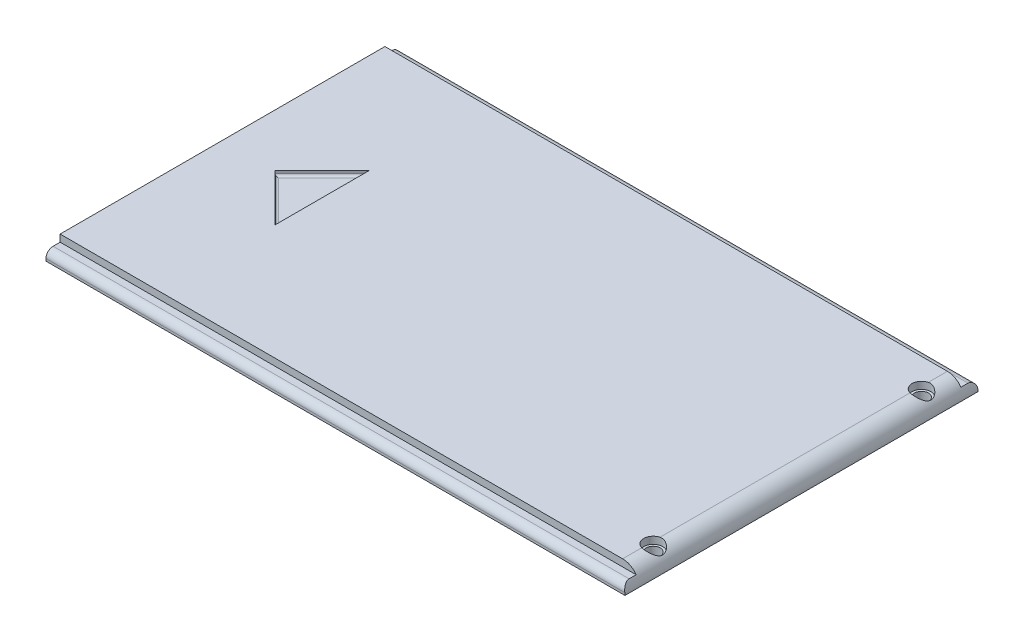
SolidWorks part; units mm, degrees
ref_plane "Front" through (0, 0, 0) normal (0, 0, 1) x (1, 0, 0)
ref_plane "Top" through (0, 0, 0) normal (0, 1, 0) x (1, 0, 0)
ref_plane "Right" through (0, 0, 0) normal (1, 0, 0) x (0, 0, -1)
sketch "Sketch1" plane through (0, 0, 0) normal (0, 1, 0) x (1, 0, 0)
  line L1 (-55, 37.5) -> (68, 37.5)
  line L2 (-55, 37.5) -> (-55, -37.5)
  line L3 (-55, -37.5) -> (68, -37.5)
  line L4 (68, 37.5) -> (68, -37.5)
  dimension "D1" = 37.5
  dimension "D2" = 75
  dimension "D3" = 123
  dimension "D4" = 55
extrude "Boss-Extrude1" add sketch "Sketch1" against normal blind 3.5
sketch "Sketch2" plane through (0, 0, 0) normal (0, 1, 0) x (1, 0, 0)
  line L0 (68, -37.5) -> (68, 37.5) construction
  line L1 (-55, 37.5) -> (68, 37.5)
  line L2 (-55, 37.5) -> (-55, 34.5)
  line L3 (-55, 34.5) -> (68, 34.5)
  line L4 (68, 37.5) -> (68, 34.5)
  line L6 (-55, -37.5) -> (68, -37.5)
  line L7 (-55, -37.5) -> (-55, -34.5)
  line L8 (-55, -34.5) -> (68, -34.5)
  line L9 (68, -37.5) -> (68, -34.5)
  dimension "D1" = 3
  dimension "D2" = 3
extrude "Cut-Extrude2" cut sketch "Sketch2" against normal blind 1.5
fillet "Fillet1" radius 1.5 1 edges at (6.5, -1.5, 37.5)
fillet "Fillet2" radius 1.5 1 edges at (6.5, -1.5, -37.5)
fillet "Fillet3" radius 3.5 9 edges at (68, 0, 0) (68, -1.5, -35.25) (68, -0.75, -34.5) (68, -0.75, 34.5) (68, -1.5, 35.25) (68, -1.9393, 37.0607) (68, -1.9393, -37.0607) (68, -3.25, -37.5) (68, -3.25, 37.5)
sketch "Sketch3" plane through (0, 0, 0) normal (0, 1, 0) x (1, 0, 0)
  line L0 (-43.8527, 0) -> (-33.8527, -10)
  line L1 (-33.8527, -10) -> (-33.8527, 10)
  line L2 (-33.8527, 10) -> (-43.8527, 0)
  point P2 (-33.8527, 0)
  dimension "D1" = 20
  dimension "D2" = 0
extrude "Cut-Extrude3" cut sketch "Sketch3" against normal blind 1
fillet "Fillet4" radius 0.5 3 edges at (-33.8527, -1, 0) (-38.8527, -1, 5) (-38.8527, -1, -5)
sketch "Sketch9" plane through (0, 0, 0) normal (0, 1, 0) x (1, 0, 0)
  line L0 (67.9641, -37.5) -> (-55, -37.5) construction
  line L1 (68, -37.5) -> (68, 37.5) construction
  line L2 (-55, 37.5) -> (67.9641, 37.5) construction
  circle A0 centre (65, -28.5) radius 2
  circle A1 centre (65, 28.5) radius 2
  dimension "D3" = 4
  dimension "D4" = 4
  dimension "D1" = 9
  dimension "D2" = 3
  dimension "D5" = 9
  dimension "D6" = 3
extrude "Cut-Extrude4" cut sketch "Sketch9" against normal blind 1.5
sketch "Sketch10" plane through (0, 0, 0) normal (0, 1, 0) x (1, 0, 0)
  line L0 (68, -37.5) -> (68, 37.5) construction
  line L2 (-55, 37.5) -> (67.9641, 37.5) construction
  circle A0 centre (65, 28.5) radius 1.5
  circle A1 centre (65, -28.5) radius 1.5
  dimension "D3" = 3
  dimension "D4" = 3
  dimension "D1" = 3
  dimension "D2" = 9
extrude "Cut-Extrude5" cut sketch "Sketch10" against normal through all
